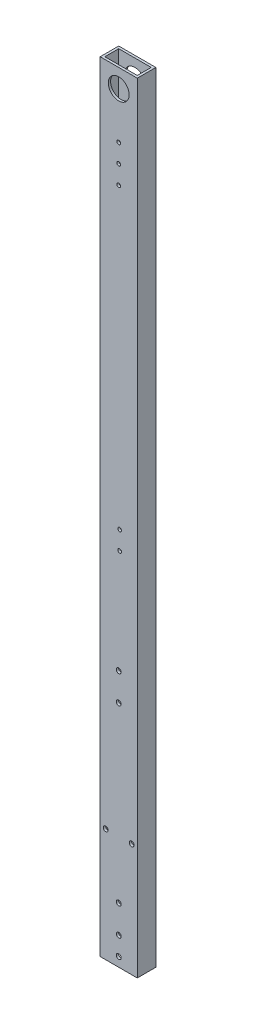
SolidWorks part; units mm, degrees
material "5052-O"
ref_plane "Front Plane" through (0, 0, 0) normal (0, 0, 1) x (1, 0, 0)
ref_plane "Top Plane" through (0, 0, 0) normal (0, 1, 0) x (1, 0, 0)
ref_plane "Right Plane" through (0, 0, 0) normal (1, 0, 0) x (0, 0, -1)
sketch "Sketch1" plane through (0, 0, 0) normal (0, 1, 0) x (1, 0, 0)
  line L0 (-22.225, 9.525) -> (22.225, 9.525)
  line L1 (-25.4, -12.7) -> (25.4, -12.7)
  line L2 (-25.4, -12.7) -> (-25.4, 12.7)
  line L3 (-25.4, 12.7) -> (25.4, 12.7)
  line L4 (25.4, -12.7) -> (25.4, 12.7)
  line L5 (-25.4, -12.7) -> (25.4, 12.7) construction
  line L6 (-25.4, 12.7) -> (25.4, -12.7) construction
  line L7 (22.225, -9.525) -> (22.225, 9.525)
  line L8 (-22.225, -9.525) -> (22.225, -9.525)
  line L9 (-22.225, -9.525) -> (-22.225, 9.525)
  point P0 (0, 0)
  dimension "D1" = 25.4
  dimension "D2" = 50.8
  dimension "D3" = 3.175
extrude "Boss-Extrude1" add sketch "Sketch1" along normal blind 1066.8
sketch "Sketch2" plane through (0, 0, 12.7) normal (0, 0, 1) x (1, 0, 0)
  line L0 (-25.4, 1066.8) -> (25.4, 1066.8) construction
  line L1 (0, 1041.4) -> (0, 1066.8) construction
  circle A0 centre (0, 1041.4) radius 14.2875
  dimension "D1" = 28.575
  dimension "D2" = 25.4
extrude "Cut-Extrude1" cut sketch "Sketch2" against normal through all
sketch "Sketch3" plane through (0, 0, 12.7) normal (0, 0, 1) x (1, 0, 0)
  line L0 (0, 313.436) -> (0, 0) construction
  circle A0 centre (0, 313.436) radius 3.3734
  circle A1 centre (0, 1041.4) radius 14.2875 construction
  dimension "D1" = 727.964
  dimension "D2" = 6.7469
extrude "Cut-Extrude2" cut sketch "Sketch3" against normal through all
sketch "Sketch4" plane through (0, 0, 12.7) normal (0, 0, 1) x (1, 0, 0)
  line L0 (0, 351.536) -> (0, 0) construction
  circle A0 centre (0, 351.536) radius 3.3734
  circle A1 centre (0, 313.436) radius 3.3734 construction
  dimension "D1" = 6.7469
  dimension "D2" = 38.1
extrude "Cut-Extrude3" cut sketch "Sketch4" against normal through all
sketch "Sketch5" plane through (0, 0, 12.7) normal (0, 0, 1) x (1, 0, 0)
  line L0 (0, 41.4734) -> (0, 0) construction
  line L1 (-25.4, 0) -> (25.4, 0) construction
  circle A0 centre (0, 12.7) radius 3.3734
  circle A1 centre (0, 38.1) radius 3.3734
  dimension "D1" = 6.7469
  dimension "D2" = 6.7469
  dimension "D3" = 12.7
  dimension "D4" = 25.4
extrude "Cut-Extrude4" cut sketch "Sketch5" against normal through all
hole_wizard "13/64 (0.20313) Diameter Hole1" positions "Sketch6" profile "Sketch7" hole size "13/64" standard "ANSI Inch" end condition through all
sketch "Sketch6" plane through (0, 0, -12.7) normal (0, 0, -1) x (-1, 0, 0)
  point P0 (-1.27, 519.5854)
  point P3 (-1.27, 494.1854)
sketch "Sketch7" plane through (1.27, 519.5854, -12.7) normal (1, 0, 0) x (0, 1, 0)
  line L0 (0, 0) -> (0, 25.4)
  line L1 (0, 25.4) -> (2.5798, 25.4)
  line L2 (2.5798, 25.4) -> (2.5798, 0)
  line L5 (2.5798, 0) -> (0, 0)
  line L11 (0, -6.35) -> (0, 107.95) construction
  dimension "Thru Hole Dia." = 5.1595
  dimension "Thru Hole Depth" = 25.4
hole_wizard "13/64 (0.20313) Diameter Hole2" positions "Sketch8" profile "Sketch9" hole size "13/64" standard "ANSI Inch" end condition through all
sketch "Sketch8" plane through (0, 0, -12.7) normal (0, 0, -1) x (-1, 0, 0)
  point P0 (0, 977.9)
  point P3 (0, 952.5)
  point P6 (0, 927.1)
sketch "Sketch9" plane through (0, 977.9, -12.7) normal (1, 0, 0) x (0, 1, 0)
  line L0 (0, 0) -> (0, 25.4)
  line L1 (0, 25.4) -> (2.5798, 25.4)
  line L2 (2.5798, 25.4) -> (2.5798, 0)
  line L5 (2.5798, 0) -> (0, 0)
  line L11 (0, -6.35) -> (0, 107.95) construction
  dimension "Thru Hole Dia." = 5.1595
  dimension "Thru Hole Depth" = 25.4
sketch "Sketch10" plane through (0, 0, -12.7) normal (0, 0, -1) x (-1, 0, 0)
  line L0 (-25.4, 0) -> (25.4, 0) construction
  circle A0 centre (0, 76.2) radius 3.3734
  dimension "D1" = 6.7469
  dimension "D2" = 76.2
extrude "Cut-Extrude5" cut sketch "Sketch10" against normal through all
sketch "Sketch11" plane through (0, 0, -12.7) normal (0, 0, -1) x (-1, 0, 0)
  circle A0 centre (-17.78, 155.1754) radius 3.3734
  circle A1 centre (17.78, 155.1754) radius 3.3734
extrude "Cut-Extrude6" cut sketch "Sketch11" against normal through all
sketch "Sketch12" plane through (0, 0, -12.7) normal (0, 0, -1) x (-1, 0, 0)
  line L0 (0, 0) -> (0, 1066.8) construction
  line L1 (-25.4, 1066.8) -> (25.4, 1066.8) construction
  line L2 (-25.4, 0) -> (25.4, 0) construction
  circle A0 centre (0, 114.3) radius 2.5797
  circle A1 centre (0, 254) radius 2.5797
  dimension "D1" = 5.1594
  dimension "D2" = 5.1594
  dimension "D3" = 114.3
  dimension "D4" = 139.7
